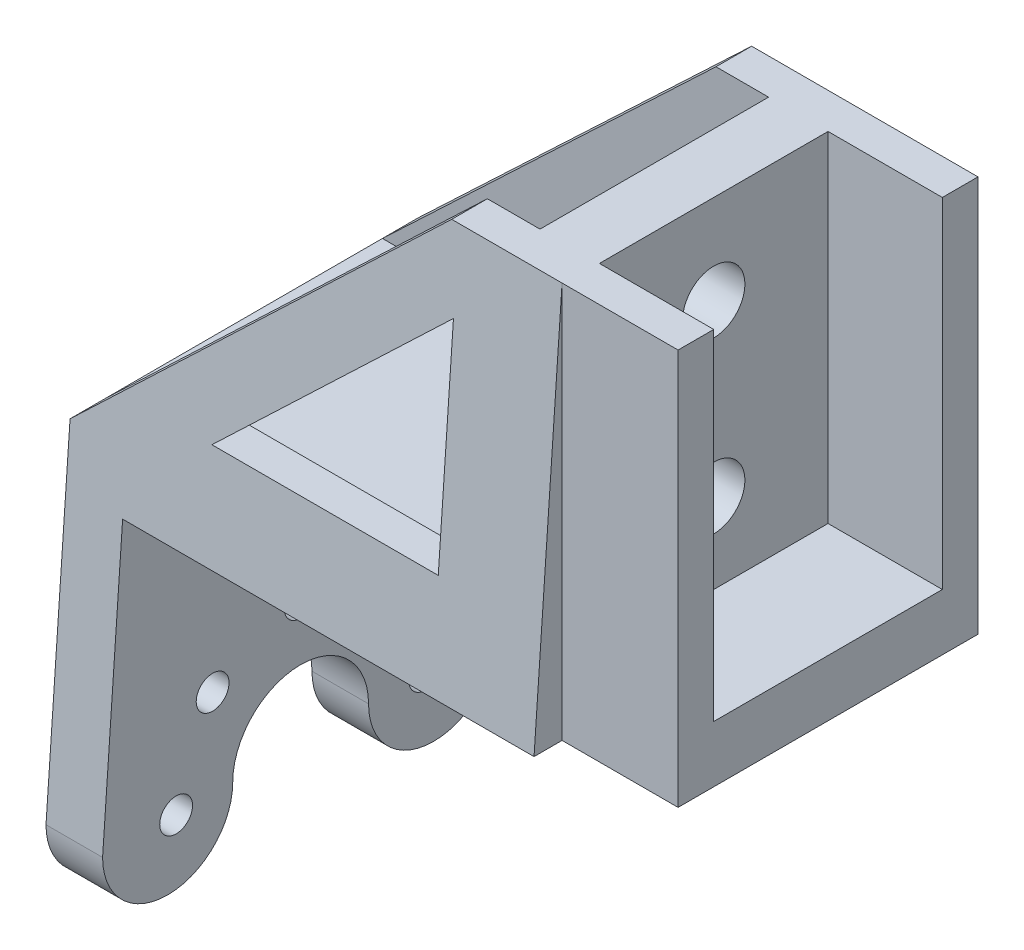
SolidWorks part; units mm, degrees
ref_plane "前视基准面" through (0, 0, 0) normal (0, 0, 1) x (1, 0, 0)
ref_plane "上视基准面" through (0, 0, 0) normal (0, 1, 0) x (1, 0, 0)
ref_plane "右视基准面" through (0, 0, 0) normal (1, 0, 0) x (0, 0, -1)
sketch "草图1" plane through (0, 0, 0) normal (0, 0, 1) x (1, 0, 0)
  line L0 (-2.4052, -0.0763) -> (-130.7806, -0.0763) construction
  line L1 (0, 0) -> (0, 37.5806) construction
  line L7 (51.6, -0.0763) -> (51.6, 29.9237)
  line L8 (51.6, 29.9237) -> (20, 59.9237)
  line L9 (20, 59.9237) -> (-20, 59.9237)
  line L10 (-20, 59.9237) -> (-51.6, 29.9237)
  line L11 (-51.6, 29.9237) -> (-51.6, -0.0763)
  line L12 (-51.6, -0.0763) -> (51.6, -0.0763)
  dimension "D1" = 103.2
  dimension "D2" = 60
  dimension "D5" = 30
  dimension "D6" = 40
extrude "凸台-拉伸1" add sketch "草图1" along normal blind 35
sketch "草图6" plane through (-51.6, 0, 0) normal (-1, 0, 0) x (0, 0, 1)
  line L0 (35, -0.0763) -> (0, -0.0763) construction
  circle A0 centre (17.5, -0.0763) radius 6
  dimension "D1" = 12
extrude "切除-拉伸2" cut sketch "草图6" against normal up to surface (103.2 mm away) up to face at (51.6, 14.9237, 17.5)
sketch "草图7" plane through (-51.6, 0, 0) normal (-1, 0, 0) x (0, 0, 1)
  line L0 (11.5, -0.0763) -> (0, -0.0763) construction
  line L1 (35, -0.0763) -> (23.5, -0.0763) construction
  circle A0 centre (5.75, -0.0763) radius 5.75
  circle A1 centre (29.25, -0.0763) radius 5.75
extrude "凸台-拉伸3" add sketch "草图7" against normal up to surface (103.2 mm away) up to face at (51.6, 10.9237, 17.5)
sketch "草图8" plane through (0, 0, 35) normal (0, 0, 1) x (1, 0, 0)
  line L0 (0, -0.0763) -> (0, 61.1377) construction
  line L2 (-46.6, -0.0763) -> (-46.6, 24.9237)
  line L3 (-51.6, -0.0763) -> (51.6, -0.0763) construction
  line L4 (-46.6, 24.9237) -> (46.6, 24.9237)
  line L5 (46.6, 24.9237) -> (46.6, -0.0763)
  line L7 (-46.6, -0.0763) -> (-46.6, -12.1113)
  line L8 (-46.6, -12.1113) -> (46.6, -12.1113)
  line L9 (46.6, -12.1113) -> (46.6, -0.0763)
  dimension "D1" = 93.2
  dimension "D2" = 25
extrude "切除-拉伸3" cut sketch "草图8" against normal up to surface (35 mm away) up to face at (0, 29.9237, 0)
hole_wizard "M2.5 Clearance Hole1" positions "草图12" profile "草图13" hole size "M2.5" standard "ISO" end condition through all
sketch "草图12" plane through (51.6, 0, 0) normal (1, 0, 0) x (0, 0, -1)
  line L0 (-17.5, 29.9237) -> (-17.5, -2.5018) construction
  line L3 (-29.25, -0.0763) -> (-5.5955, -0.0763) construction
  circle A1 centre (-17.5, -0.0763) radius 0.7969 construction
  point P44 (-28.5, -0.0763)
  point P72 (-25.2782, 7.7019)
  point P73 (-17.5, 10.9237)
  point P74 (-9.7218, 7.7019)
  point P75 (-6.5, -0.0763)
  dimension "D1" = 11
  dimension "D2" = 5
sketch "草图13" plane through (51.6, -0.0763, 28.5) normal (0, 1, 0) x (0, 0, -1)
  line L0 (0, 0) -> (0, 103.2)
  line L1 (0, 103.2) -> (1.45, 103.2)
  line L2 (1.45, 103.2) -> (1.45, 0.025)
  line L3 (1.45, 0.025) -> (1.475, 0)
  line L5 (1.475, 0) -> (0, 0)
  line L6 (-1.45, 0.025) -> (-1.475, 0) construction
  line L11 (0, -6.35) -> (0, 107.95) construction
  dimension "通孔孔直径" = 2.9
  dimension "通孔孔深度" = 103.2
  dimension "近端锥形沉头孔直径" = 2.95
  dimension "近端锥形沉头孔角度" = 90
sketch "草图16" plane through (0, 59.9237, 0) normal (0, 1, 0) x (1, 0, 0)
  line L0 (0, 0) -> (0, -35) construction
  line L3 (-20, -17.5) -> (20, -17.5) construction
  line L4 (-10.1, -7.4) -> (10.1, -7.4)
  line L5 (-10.1, -7.4) -> (-10.1, -27.6)
  line L6 (-10.1, -27.6) -> (10.1, -27.6)
  line L7 (10.1, -7.4) -> (10.1, -27.6)
  dimension "D1" = 20.2
  dimension "D2" = 20.2
extrude "切除-拉伸5" cut sketch "草图16" against normal blind 30
sketch "草图15" plane through (0, 0, 35) normal (0, 0, 1) x (1, 0, 0)
  line L0 (0, 24.9237) -> (0, 61.498) construction
  line L2 (0, 24.9237) -> (-10.25, 24.9237)
  line L3 (46.6, 24.9237) -> (-46.6, 24.9237) construction
  line L4 (-10.25, 24.9237) -> (-10.25, 59.9237)
  line L5 (20, 59.9237) -> (-20, 59.9237) construction
  line L6 (-10.25, 59.9237) -> (10.25, 59.9237)
  line L7 (10.25, 59.9237) -> (10.25, 24.9237)
  line L8 (10.25, 24.9237) -> (-10.25, 24.9237)
  dimension "D1" = 20.5
extrude "切除-拉伸6" cut sketch "草图15" against normal blind 4.25 contours L4 L6 L7 L8
sketch "草图17" plane through (0, 0, 0) normal (0, 0, -1) x (-1, 0, 0)
  line L4 (-10.25, 24.9237) -> (10.25, 24.9237)
  line L5 (-10.25, 59.9237) -> (-10.25, 24.9237)
  line L6 (10.25, 59.9237) -> (-10.25, 59.9237)
  line L7 (10.25, 24.9237) -> (10.25, 59.9237)
  line L8 (-10.25, 24.9237) -> (10.25, 24.9237)
  line L9 (-10.25, 59.9237) -> (-10.25, 24.9237)
  line L10 (10.25, 59.9237) -> (-10.25, 59.9237)
  line L11 (10.25, 24.9237) -> (10.25, 59.9237)
  dimension "D1" = 0
extrude "切除-拉伸7" cut sketch "草图17" against normal blind 4.25
hole_wizard "M5 Clearance Hole1" [suppressed] positions "草图18" profile "草图19" hole size "M5" standard "ISO"
sketch "草图18" plane through (0, 0, 4.25) normal (0, 0, -1) x (-1, 0, 0)
  line L0 (0, 24.9237) -> (0, 65.7443) construction
  line L3 (0, 29.9237) -> (-37.1771, 29.9237) construction
  line L5 (-10.25, 24.9237) -> (10.25, 24.9237) construction
  point P18 (0, 35.9237)
  point P20 (0, 50.9237)
  dimension "D1" = 5
  dimension "D2" = 15
  dimension "D3" = 6
sketch "草图19" plane through (0, 50.9237, 4.25) normal (1, 0, 0) x (0, 1, 0)
  line L0 (0, 0) -> (0, 30.75)
  line L1 (0, 30.75) -> (2.75, 30.75)
  line L2 (2.75, 30.75) -> (2.75, 0.025)
  line L3 (2.75, 0.025) -> (2.775, 0)
  line L5 (2.775, 0) -> (0, 0)
  line L6 (-2.75, 0.025) -> (-2.775, 0) construction
  line L11 (0, -6.35) -> (0, 107.95) construction
  dimension "通孔孔直径" = 5.5
  dimension "通孔孔深度" = 30.75
  dimension "近端锥形沉头孔直径" = 5.55
  dimension "近端锥形沉头孔角度" = 90
sketch "草图20" plane through (51.6, 0, 0) normal (1, 0, 0) x (0, 0, -1)
  line L0 (-30.75, 59.9237) -> (-35, 59.9237) construction
  line L1 (-30.75, 59.9237) -> (-35, 59.9237)
  line L2 (-30.75, 59.9237) -> (-35, -0.0763)
  line L3 (-35, -0.0763) -> (-35, 59.9237)
  line L4 (-17.5, 59.9237) -> (-17.5, 49.5416) construction
  line L6 (0, -0.0763) -> (0, 59.9237)
  line L7 (-4.25, 59.9237) -> (0, -0.0763)
  line L8 (-4.25, 59.9237) -> (0, 59.9237)
extrude "切除-拉伸8" cut sketch "草图20" against normal up to surface (103.2 mm away) up to face at (-51.6, -0.0763, 27.05)
sketch "草图21" plane through (51.6, 0, 0) normal (1, 0, 0) x (0, 0, -1)
  line L0 (-27.6, 59.9237) -> (-29.725, 29.9237)
  line L1 (-17.5, 59.9237) -> (-17.5, 29.9237) construction
  line L3 (-32.875, 29.9237) -> (-2.125, 29.9237) construction
  line L4 (-29.725, 29.9237) -> (-5.275, 29.9237)
  line L5 (-27.6, 59.9237) -> (-7.4, 59.9237)
  line L6 (-30.75, 59.9237) -> (-4.25, 59.9237) construction
  line L7 (-7.4, 59.9237) -> (-5.275, 29.9237)
  line L8 (-30.75, 59.9237) -> (-32.875, 29.9237) construction
  point P10 (-17.5, 29.9237)
  point P11 (-17.5, 59.9237)
  dimension "D1" = 0
extrude "切除-拉伸9" cut sketch "草图21" against normal blind 36.25 contours L4 L7 L5 L0
sketch "草图22" plane through (-51.6, 0, 0) normal (-1, 0, 0) x (0, 0, 1)
  line L4 (29.725, 29.9237) -> (27.6, 59.9237)
  line L5 (5.275, 29.9237) -> (29.725, 29.9237)
  line L6 (7.4, 59.9237) -> (5.275, 29.9237)
  line L7 (27.6, 59.9237) -> (7.4, 59.9237)
  line L8 (29.725, 29.9237) -> (27.6, 59.9237)
  line L9 (5.275, 29.9237) -> (29.725, 29.9237)
  line L10 (7.4, 59.9237) -> (5.275, 29.9237)
  line L11 (27.6, 59.9237) -> (7.4, 59.9237)
  dimension "D1" = 0
extrude "切除-拉伸10" cut sketch "草图22" against normal blind 36.25
sketch "草图23" [suppressed] plane through (-15.35, 0, 0) normal (-1, 0, 0) x (0, 0, 1)
  line L0 (17.5, 59.9237) -> (17.5, 29.9237) construction
  line L3 (13.5, 34.9237) -> (21.5, 34.9237)
  line L4 (10.5, 37.9237) -> (10.5, 51.9237)
  line L5 (17.65, 44.9237) -> (-13.119, 44.9237) construction
  line L6 (5.275, 29.9237) -> (29.725, 29.9237) construction
  line L7 (13.5, 54.9237) -> (21.5, 54.9237)
  line L8 (24.5, 37.9237) -> (24.5, 51.9237)
  arc A0 (10.5, 37.9237) -> (13.5, 34.9237) centre (13.5, 37.9237) ccw
  arc A1 (10.5, 31.9237) -> (13.5, 34.9237) centre (13.5, 31.9237) cw
  arc A2 (10.5, 51.9237) -> (13.5, 54.9237) centre (13.5, 51.9237) cw
  arc A3 (24.5, 37.9237) -> (21.5, 34.9237) centre (21.5, 37.9237) cw
  arc A4 (24.5, 51.9237) -> (21.5, 54.9237) centre (21.5, 51.9237) ccw
  point P20 (10.5, 44.9237)
  point P21 (17.5, 34.9237)
  point P26 (17.5, 54.9237)
  dimension "D1" = 3
  dimension "D2" = 15
  dimension "D3" = 7
  dimension "D4" = 4
extrude "切除-拉伸11" [suppressed] cut sketch "草图23" against normal up to surface (30.7 mm away) contours L3 A3 L8 A4 L7 A2 L4 A0
sketch "草图25" plane through (0, 0, 0) normal (0, 0, 1) x (1, 0, 0)
  line L0 (15.35, 59.9237) -> (20, 59.9237) construction
  line L1 (15.35, 59.9237) -> (15.35, 29.9237) construction
  line L2 (15.35, 29.9237) -> (51.6, 29.9237) construction
  line L3 (15.35, 59.9237) -> (20, 59.9237) construction
  line L4 (15.35, 59.9237) -> (15.35, 29.9237) construction
  line L5 (15.35, 29.9237) -> (51.6, 29.9237) construction
  line L6 (39.35, 33.9237) -> (19.35, 33.9237)
  line L7 (19.35, 33.9237) -> (19.35, 52.9111)
  line L8 (19.35, 52.9111) -> (39.35, 33.9237)
  line L9 (0, 59.9237) -> (0, 24.9237) construction
  line L10 (15.35, 29.9237) -> (51.6, 29.9237)
  line L11 (15.35, 59.9237) -> (15.35, 29.9237)
  line L12 (20, 59.9237) -> (15.35, 59.9237)
  line L13 (51.6, 29.9237) -> (20, 59.9237)
  line L14 (15.35, 29.9237) -> (51.6, 29.9237) construction
  line L15 (15.35, 59.9237) -> (15.35, 29.9237) construction
  line L16 (20, 59.9237) -> (15.35, 59.9237) construction
  line L17 (51.6, 29.9237) -> (20, 59.9237) construction
  line L18 (-19.35, 52.9111) -> (-39.35, 33.9237)
  line L19 (-19.35, 33.9237) -> (-19.35, 52.9111)
  line L20 (-39.35, 33.9237) -> (-19.35, 33.9237)
  dimension "D2" = 4
  dimension "D3" = 4
  dimension "D4" = 20
  dimension "D1" = 0
extrude "切除-拉伸12" cut sketch "草图25" along normal through all
ref_plane "Plane1" through (0, 0, 0) normal (1, 0, 0) x (0, 0, -1)
sketch "Sketch1" plane through (51.6, 0, 0) normal (1, 0, 0) x (0, 0, -1)
  line L0 (-29.725, 29.9237) -> (-5.275, 29.9237) construction
  line L1 (7.5, -10.0763) -> (-42.5, -10.0763)
  line L2 (7.5, -10.0763) -> (7.5, 69.9237)
  line L3 (7.5, 69.9237) -> (-42.5, 69.9237)
  line L4 (-42.5, -10.0763) -> (-42.5, 69.9237)
  line L5 (7.5, -10.0763) -> (-42.5, 69.9237) construction
  line L6 (7.5, 69.9237) -> (-42.5, -10.0763) construction
  point P0 (-17.5, 29.9237)
  dimension "D1" = 50
  dimension "D2" = 80
extrude "Cut-Extrude1" cut sketch "Sketch1" against normal up to surface (51.6 mm away)
sketch "Sketch2" plane through (-15.35, 0, 0) normal (-1, 0, 0) x (0, 0, 1)
  line L0 (17.5, 29.9237) -> (17.5, 59.9237) construction
  line L1 (5.275, 29.9237) -> (29.725, 29.9237) construction
  line L2 (27.6, 59.9237) -> (7.4, 59.9237) construction
  point P6 (17.5, 51.9237)
  point P7 (17.5, 36.9237)
  dimension "D1" = 15
  dimension "D2" = 7
hole_wizard "M5 Clearance Hole2" positions "Sketch2" profile "Sketch3" hole size "M5" standard "ISO" end condition through all
sketch "Sketch3" plane through (-15.35, 36.9237, 17.5) normal (0, 1, 0) x (0, 0, 1)
  line L0 (0, 0) -> (0, 15.35)
  line L1 (0, 15.35) -> (2.75, 15.35)
  line L2 (2.75, 15.35) -> (2.75, 0.025)
  line L3 (2.75, 0.025) -> (2.775, 0)
  line L5 (2.775, 0) -> (0, 0)
  line L6 (-2.75, 0.025) -> (-2.775, 0) construction
  line L11 (0, -6.35) -> (0, 107.95) construction
  dimension "Thru Hole Dia." = 5.5
  dimension "Thru Hole Depth" = 15.35
  dimension "Near C'Sink Dia." = 5.55
  dimension "Near C'Sink Angle" = 90
